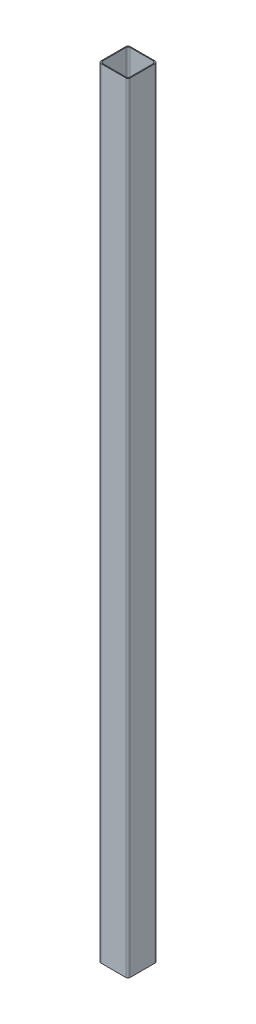
SolidWorks part; units mm, degrees
ref_plane "Plano frontal" through (0, 0, 0) normal (0, 0, 1) x (1, 0, 0)
ref_plane "Plano superior" through (0, 0, 0) normal (0, 1, 0) x (1, 0, 0)
ref_plane "Plano direito" through (0, 0, 0) normal (1, 0, 0) x (0, 0, -1)
sketch "Esboço1" plane through (0, 0, 0) normal (0, 1, 0) x (1, 0, 0)
  line L0 (-18.8, -18.8) -> (-18.8, 18.8)
  line L1 (20, -20) -> (-20, -20)
  line L2 (20, -20) -> (20, 20)
  line L3 (20, 20) -> (-20, 20)
  line L4 (-20, -20) -> (-20, 20)
  line L5 (20, -20) -> (-20, 20) construction
  line L6 (20, 20) -> (-20, -20) construction
  line L7 (18.8, 18.8) -> (-18.8, 18.8)
  line L8 (18.8, -18.8) -> (18.8, 18.8)
  line L9 (18.8, -18.8) -> (-18.8, -18.8)
  point P0 (0, 0)
  dimension "D1" = 40
  dimension "D2" = 40
  dimension "D3" = 1.2
extrude "Ressalto-extrusão1" add sketch "Esboço1" along normal mid plane 1060
fillet "Filete1" radius 3 8 edges at (-20, 0, -20) (20, 0, -20) (18.8, 0, -18.8) (18.8, 0, 18.8) (-18.8, 0, 18.8) (-18.8, 0, -18.8) (-20, 0, 20) (20, 0, 20)
